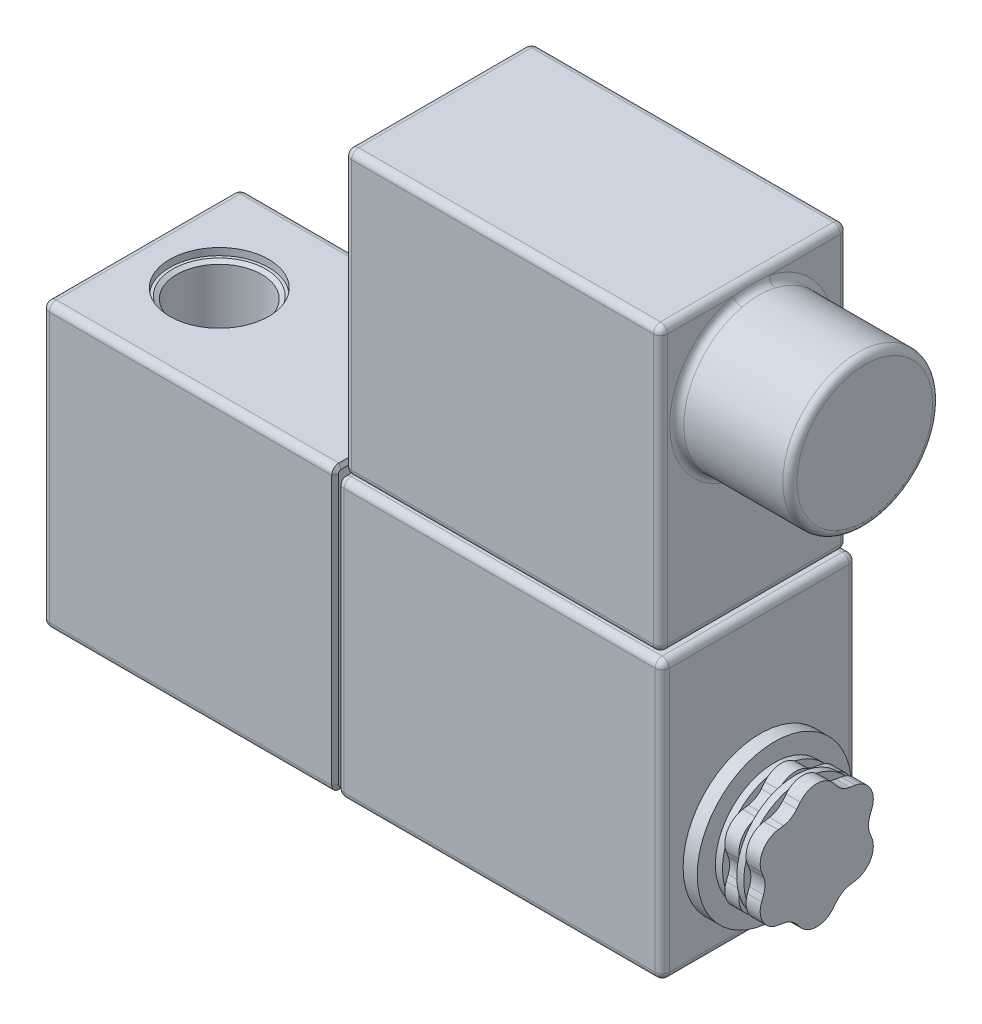
SolidWorks part; units mm, degrees
ref_plane "Front Plane" through (0, 0, 0) normal (0, 0, 1) x (1, 0, 0)
ref_plane "Top Plane" through (0, 0, 0) normal (0, 1, 0) x (1, 0, 0)
ref_plane "Right Plane" through (0, 0, 0) normal (1, 0, 0) x (0, 0, -1)
sketch "草图1" plane through (0, 0, 0) normal (0, 1, 0) x (1, 0, 0)
  line L0 (0, 0) -> (0, 14)
  line L1 (0, 14) -> (20.6512, 14)
  line L2 (20.6512, 14) -> (20.6512, 0)
  line L3 (20.6512, 0) -> (0, 0)
extrude "凸台-拉伸1" add sketch "草图1" along normal blind 20
sketch "草图2" plane through (20.6512, 0, 0) normal (1, 0, 0) x (0, 0, -1)
  circle A0 centre (6.862, 7.8279) radius 5.855
extrude "凸台-拉伸3" add sketch "草图2" along normal blind 0.2 contours A0
sketch "草图3" plane through (20.8512, 0, 0) normal (1, 0, 0) x (0, 0, -1)
  line L1 (0, 0) -> (13.7246, 0)
  line L2 (0, 0) -> (0, 19.6113)
  line L3 (0, 19.6113) -> (13.7246, 19.6113)
  line L4 (13.7246, 0) -> (13.7246, 19.6113)
extrude "凸台-拉伸4" add sketch "草图3" along normal blind 23
sketch "草图4" plane through (0, 19.6113, 0) normal (0, 1, 0) x (1, 0, 0)
  circle A0 centre (31.5415, 6.4634) radius 5.0766
extrude "凸台-拉伸5" add sketch "草图4" along normal blind 0.2
sketch "草图5" plane through (0, 19.8113, 0) normal (0, 1, 0) x (1, 0, 0)
  line L1 (43.5159, 0.2129) -> (21.1667, 0.2129)
  line L2 (43.5159, 0.2129) -> (43.5159, 13.4368)
  line L3 (43.5159, 13.4368) -> (21.1667, 13.4368)
  line L4 (21.1667, 0.2129) -> (21.1667, 13.4368)
extrude "凸台-拉伸6" add sketch "草图5" along normal blind 20
fillet "圆角1" radius 0.5 4 edges at (10.3256, 0, -14) (10.3256, 20, -14) (10.3256, 0, 0) (10.3256, 20, 0)
fillet "圆角2" radius 0.5 8 edges at (0, 19.8536, -13.8536) (0, 10, -14) (0, 0.1464, -13.8536) (0, 0, -7) (0, 0.1464, -0.1464) (0, 10, 0) (0, 19.8536, -0.1464) (0, 20, -7)
fillet "圆角4" radius 0.5 12 edges at (32.3512, 19.6113, 0) (32.3512, 0, 0) (20.8512, 9.8057, 0) (43.8512, 19.6113, -6.8623) (43.8512, 0, -6.8623) (43.8512, 9.8057, 0) (32.3512, 0, -13.7246) (43.8512, 9.8057, -13.7246) (32.3512, 19.6113, -13.7246) (20.8512, 9.8057, -13.7246) (20.8512, 0, -6.8623) (20.8512, 19.6113, -6.8623)
chamfer "倒角3" distance 0.3 angle 30 8 edges at (20.6512, 0, -7) (20.6512, 0.1464, -0.1464) (20.6512, 0.1464, -13.8536) (20.6512, 10, 0) (20.6512, 10, -14) (20.6512, 19.8536, -0.1464) (20.6512, 19.8536, -13.8536) (20.6512, 20, -7)
fillet "圆角5" radius 0.5 12 edges at (32.3413, 39.8113, -0.2129) (32.3413, 19.8113, -0.2129) (21.1667, 39.8113, -6.8249) (21.1667, 29.8113, -0.2129) (21.1667, 19.8113, -6.8249) (43.5159, 29.8113, -0.2129) (43.5159, 39.8113, -6.8249) (43.5159, 19.8113, -6.8249) (43.5159, 29.8113, -13.4368) (32.3413, 39.8113, -13.4368) (21.1667, 29.8113, -13.4368) (32.3413, 19.8113, -13.4368)
sketch "草图6" plane through (43.8512, 0, 0) normal (1, 0, 0) x (0, 0, -1)
  circle A0 centre (6.9329, 6.4446) radius 5.4531
extrude "凸台-拉伸7" add sketch "草图6" along normal blind 1
sketch "草图7" plane through (44.8512, 0, 0) normal (1, 0, 0) x (0, 0, -1)
  circle A0 centre (6.9329, 6.4446) radius 4.1695
extrude "凸台-拉伸8" add sketch "草图7" along normal blind 0.5
sketch "草图8" plane through (45.3512, 0, 0) normal (1, 0, 0) x (0, 0, -1)
  line L8 (8.0988, 10.2767) -> (8.3472, 9.9699)
  line L9 (9.2787, 9.432) -> (9.6687, 9.3703)
  line L12 (10.693, 5.9067) -> (10.8346, 5.5382)
  line L13 (10.8346, 7.3509) -> (10.693, 6.9824)
  line L16 (8.3472, 2.9193) -> (8.0988, 2.6124)
  line L17 (9.6687, 3.5188) -> (9.2787, 3.4571)
  line L20 (4.5871, 3.4571) -> (4.1971, 3.5188)
  line L21 (5.767, 2.6124) -> (5.5186, 2.9193)
  line L24 (3.1728, 6.9824) -> (3.0312, 7.3509)
  line L25 (3.0312, 5.5382) -> (3.1728, 5.9067)
  line L28 (5.5186, 9.9699) -> (5.767, 10.2767)
  line L29 (4.1971, 9.3703) -> (4.5871, 9.432)
  arc A0 (9.2787, 9.432) -> (8.3472, 9.9699) centre (9.5131, 10.9136) cw
  arc A1 (5.767, 10.2767) -> (8.0988, 10.2767) centre (6.9329, 9.333) cw
  arc A2 (5.5186, 9.9699) -> (4.5871, 9.432) centre (4.3527, 10.9136) cw
  arc A3 (4.1971, 9.3703) -> (3.0312, 7.3509) centre (4.4315, 7.8888) ccw
  arc A4 (3.1728, 6.9824) -> (3.1728, 5.9067) centre (1.7725, 6.4446) cw
  arc A5 (4.1971, 3.5188) -> (3.0312, 5.5382) centre (4.4315, 5.0004) cw
  arc A6 (4.5871, 3.4571) -> (5.5186, 2.9193) centre (4.3527, 1.9755) cw
  arc A7 (8.0988, 2.6124) -> (5.767, 2.6124) centre (6.9329, 3.5562) cw
  arc A8 (9.2787, 3.4571) -> (8.3472, 2.9193) centre (9.5131, 1.9755) ccw
  arc A9 (9.6687, 3.5188) -> (10.8346, 5.5382) centre (9.4343, 5.0004) ccw
  arc A10 (10.693, 6.9824) -> (10.693, 5.9067) centre (12.0933, 6.4446) ccw
  arc A11 (10.8346, 7.3509) -> (9.6687, 9.3703) centre (9.4343, 7.8888) ccw
  dimension "D2" = 1.5
  dimension "D3" = 1.5
  dimension "D1" = 6
extrude "凸台-拉伸9" add sketch "草图8" along normal blind 1
sketch "草图9" plane through (46.3512, 0, 0) normal (1, 0, 0) x (0, 0, -1)
  circle A2 centre (6.9329, 6.4446) radius 4.1627
extrude "凸台-拉伸10" add sketch "草图9" along normal blind 0.5 contours A2
sketch "草图11" plane through (46.8512, 0, 0) normal (1, 0, 0) x (0, 0, -1)
  line L0 (8.0988, 10.2767) -> (8.3472, 9.9699)
  line L1 (9.2787, 9.432) -> (9.6687, 9.3703)
  line L2 (10.693, 5.9067) -> (10.8346, 5.5382)
  line L3 (10.8346, 7.3509) -> (10.693, 6.9824)
  line L4 (8.3472, 2.9193) -> (8.0988, 2.6124)
  line L5 (9.6687, 3.5188) -> (9.2787, 3.4571)
  line L6 (4.5871, 3.4571) -> (4.1971, 3.5188)
  line L7 (5.767, 2.6124) -> (5.5186, 2.9193)
  line L8 (3.1728, 6.9824) -> (3.0312, 7.3509)
  line L9 (3.0312, 5.5382) -> (3.1728, 5.9067)
  line L10 (5.5186, 9.9699) -> (5.767, 10.2767)
  line L11 (4.1971, 9.3703) -> (4.5871, 9.432)
  arc A0 (9.2787, 9.432) -> (8.3472, 9.9699) centre (9.5131, 10.9136) cw
  arc A1 (5.767, 10.2767) -> (8.0988, 10.2767) centre (6.9329, 9.333) cw
  arc A2 (5.5186, 9.9699) -> (4.5871, 9.432) centre (4.3527, 10.9136) cw
  arc A3 (4.1971, 9.3703) -> (3.0312, 7.3509) centre (4.4315, 7.8888) ccw
  arc A4 (3.1728, 6.9824) -> (3.1728, 5.9067) centre (1.7725, 6.4446) cw
  arc A5 (4.1971, 3.5188) -> (3.0312, 5.5382) centre (4.4315, 5.0004) cw
  arc A6 (4.5871, 3.4571) -> (5.5186, 2.9193) centre (4.3527, 1.9755) cw
  arc A7 (8.0988, 2.6124) -> (5.767, 2.6124) centre (6.9329, 3.5562) cw
  arc A8 (9.2787, 3.4571) -> (8.3472, 2.9193) centre (9.5131, 1.9755) ccw
  arc A9 (9.6687, 3.5188) -> (10.8346, 5.5382) centre (9.4343, 5.0004) ccw
  arc A10 (10.693, 6.9824) -> (10.693, 5.9067) centre (12.0933, 6.4446) ccw
  arc A11 (10.8346, 7.3509) -> (9.6687, 9.3703) centre (9.4343, 7.8888) ccw
extrude "凸台-拉伸12" add sketch "草图11" along normal blind 1
sketch "草图12" plane through (43.5159, 0, 0) normal (1, 0, 0) x (0, 0, -1)
  circle A0 centre (6.6683, 33.6583) radius 5.3
extrude "凸台-拉伸13" add sketch "草图12" along normal blind 8
fillet "圆角6" radius 0.5 2 edges at (51.5159, 33.6583, -11.9683) (43.5159, 33.6583, -1.3683)
ref_point "点1"
sketch "草图20" plane through (0, 0, 0) normal (0, -1, 0) x (-1, 0, 0)
  circle A0 centre (-5.5205, 7) radius 3.5
sketch "草图24" plane through (0, 20, 0) normal (0, 1, 0) x (1, 0, 0)
  circle A0 centre (5.5205, 7) radius 3.5
extrude "切除-拉伸5" cut sketch "草图24" against normal blind 0.5 contours A0
extrude "切除-拉伸6" cut sketch "草图20" against normal blind 0.5 contours A0
sketch "草图25" plane through (0, 19.5, 0) normal (0, 1, 0) x (1, 0, 0)
  circle A0 centre (5.5205, 7) radius 3
sketch "草图26" plane through (0, 0.5, 0) normal (0, -1, 0) x (-1, 0, 0)
  circle A0 centre (-5.5205, 7) radius 3
extrude "切除-拉伸7" cut sketch "草图26" against normal blind 7
extrude "切除-拉伸9" cut sketch "草图25" against normal blind 7 contours A0
chamfer "倒角6" distance 0.3 angle 30 1 edges at (5.5205, 19.5, -4)
chamfer "倒角7" distance 0.3 angle 30 2 edges at (5.5205, 0, -10.5) (5.5205, 0.5, -10)
scale "缩放比例1" scale about centroid uniform scaling yes scale factor 1.703704
